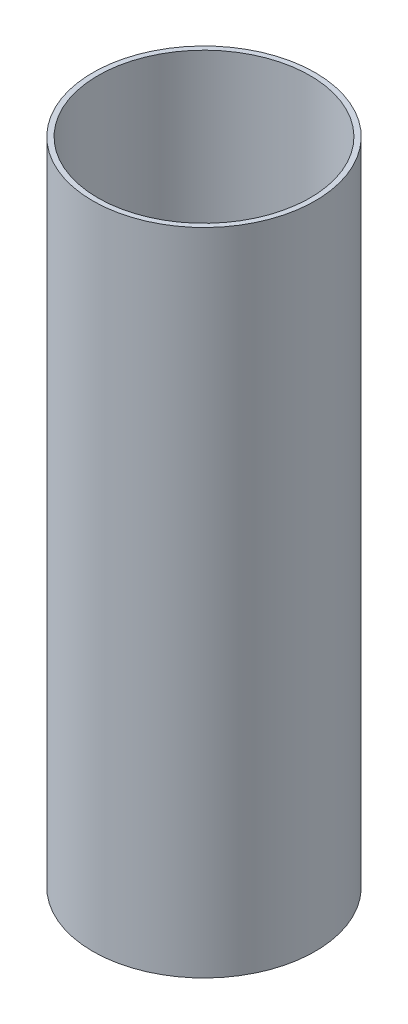
SolidWorks part; units mm, degrees
ref_plane "Plan de face" through (0, 0, 0) normal (0, 0, 1) x (1, 0, 0)
ref_plane "Plan de dessus" through (0, 0, 0) normal (0, 1, 0) x (1, 0, 0)
ref_plane "Plan de droite" through (0, 0, 0) normal (1, 0, 0) x (0, 0, -1)
sketch "Esquisse1" plane through (0, 0, 0) normal (0, 1, 0) x (1, 0, 0)
  circle A0 centre (0, 0) radius 31
  circle A1 centre (0, 0) radius 32.5
  dimension "D1" = 62
  dimension "D2" = 65
extrude "Boss.-Extru.1" add sketch "Esquisse1" along normal blind 190 contours A1 | A0
